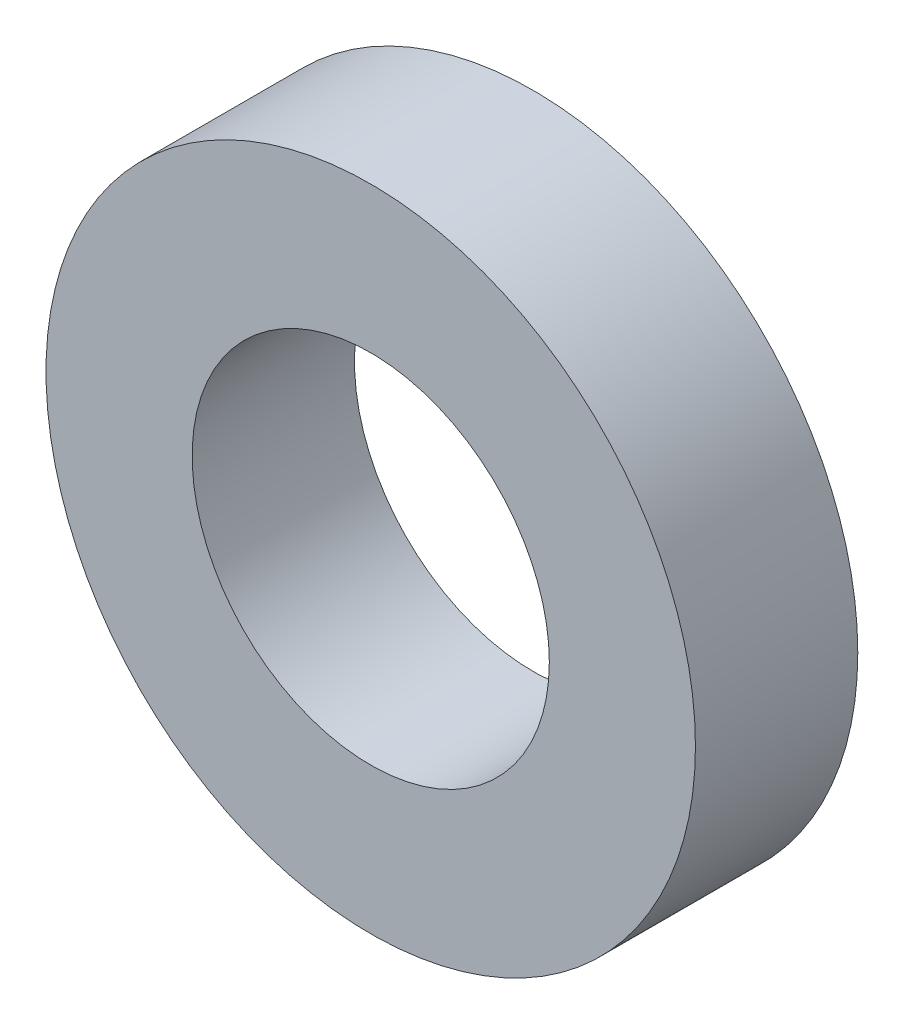
SolidWorks part; units mm, degrees
material "AISI 4340 Steel, normalized"
ref_plane "Front Plane" through (0, 0, 0) normal (0, 0, 1) x (1, 0, 0)
ref_plane "Top Plane" through (0, 0, 0) normal (0, 1, 0) x (1, 0, 0)
ref_plane "Right Plane" through (0, 0, 0) normal (1, 0, 0) x (0, 0, -1)
sketch "Sketch1" plane through (0, 0, 0) normal (0, 0, 1) x (1, 0, 0)
  circle A0 centre (0, 0) radius 2
  circle A1 centre (0, 0) radius 1.1
extrude "Spacer" add sketch "Sketch1" along normal blind 1
